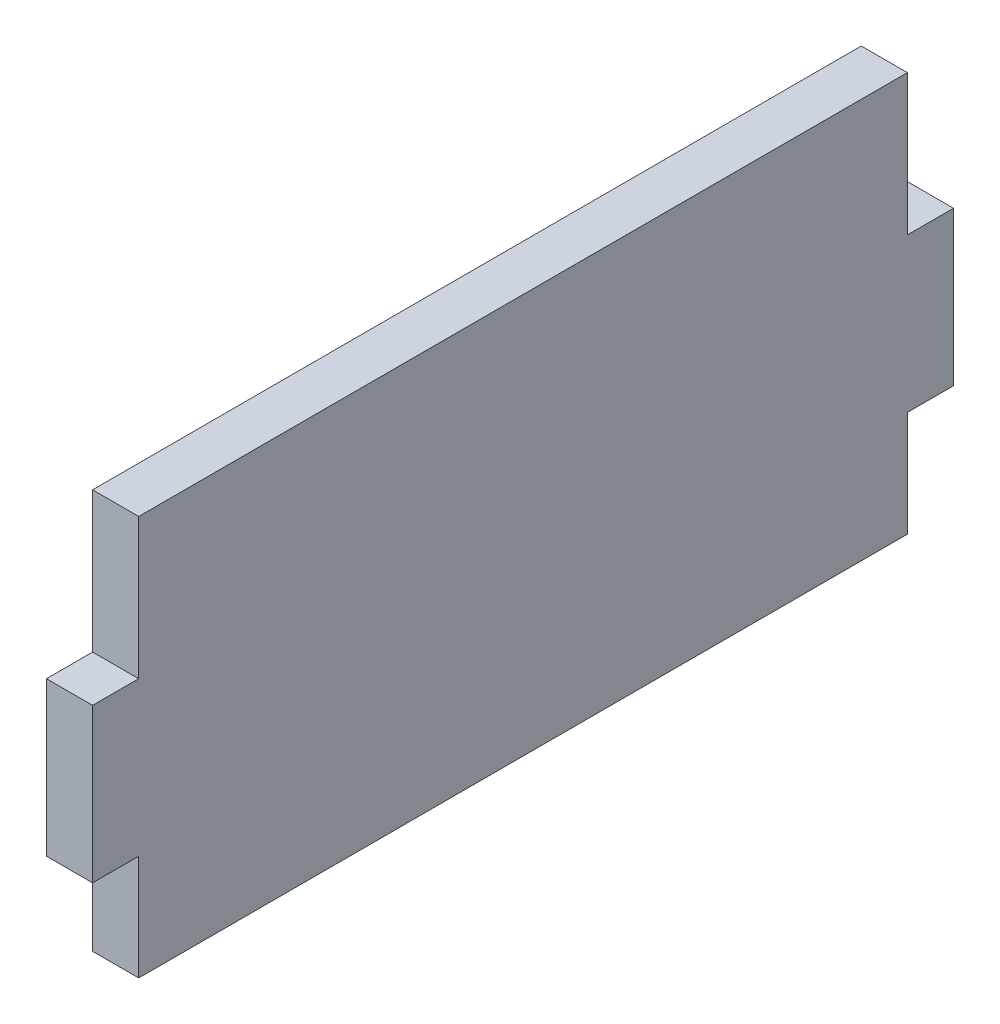
SolidWorks part; units mm, degrees
ref_plane "Front Plane" through (0, 0, 0) normal (0, 0, 1) x (1, 0, 0)
ref_plane "Top Plane" through (0, 0, 0) normal (0, 1, 0) x (1, 0, 0)
ref_plane "Right Plane" through (0, 0, 0) normal (1, 0, 0) x (0, 0, -1)
sketch "Sketch1" plane through (0, 0, 0) normal (1, 0, 0) x (0, 0, -1)
  line L0 (0, 26) -> (0, 16.86) construction
  line L1 (0, 0) -> (50, 0)
  line L2 (0, 0) -> (0, 6.86)
  line L3 (0, 26) -> (50, 26)
  line L4 (50, 0) -> (50, 6.86)
  line L5 (0, 16.86) -> (0, 26)
  line L6 (0, 16.86) -> (-3, 16.86)
  line L8 (0, 6.86) -> (-3, 6.86)
  line L9 (-3, 16.86) -> (-3, 6.86)
  line L10 (25, 0) -> (25, 26) construction
  line L11 (50, 6.86) -> (53, 6.86)
  line L12 (53, 16.86) -> (53, 6.86)
  line L13 (50, 16.86) -> (53, 16.86)
  line L14 (50, 16.86) -> (50, 26)
  dimension "D1" = 50
  dimension "D2" = 26
  dimension "D3" = 9.14
  dimension "D4" = 10
  dimension "D5" = 3
extrude "Boss-Extrude1" add sketch "Sketch1" along normal blind 3
